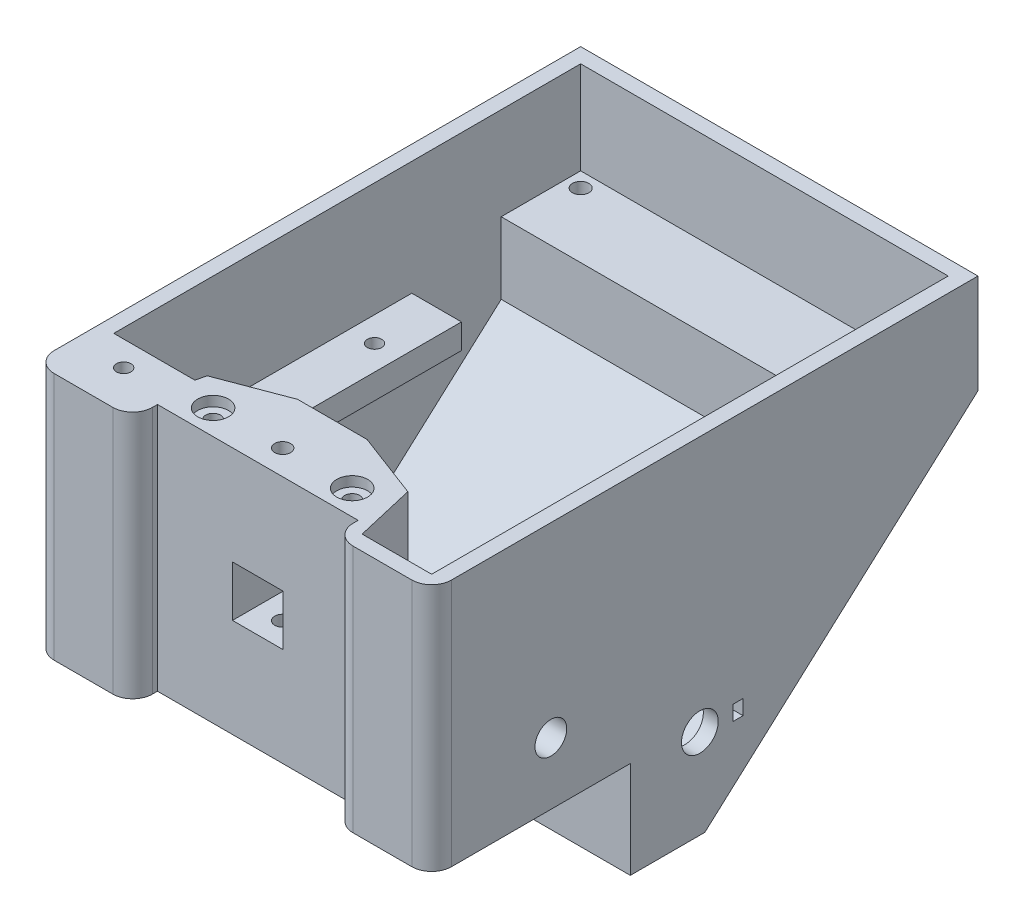
SolidWorks part; units mm, degrees
ref_plane "Спереди" through (0, 0, 0) normal (0, 0, 1) x (1, 0, 0)
ref_plane "Сверху" through (0, 0, 0) normal (0, 1, 0) x (1, 0, 0)
ref_plane "Справа" through (0, 0, 0) normal (1, 0, 0) x (0, 0, -1)
sketch "Sketch2" plane through (0, 0, 0) normal (1, 0, 0) x (0, 0, -1)
  line L0 (-27.3205, 20.9982) -> (-27.3205, -29.0018)
  line L1 (-27.3205, -29.0018) -> (12.6795, -29.0018)
  line L2 (12.6795, -29.0018) -> (12.6795, -48.5114)
  line L3 (12.6795, -48.5114) -> (27.6795, -48.5114)
  line L4 (82.6795, 20.9982) -> (82.6795, 0.9982)
  line L5 (82.6795, 20.9982) -> (-27.3205, 20.9982)
  line L6 (82.6795, 0.9982) -> (27.6795, -48.5114)
  dimension "D1" = 110
  dimension "D2" = 50
  dimension "D3" = 40
  dimension "D4" = 15
  dimension "D5" = 20
extrude "Boss-Extrude1" add sketch "Sketch2" along normal blind 80
shell "Shell1" thickness 3
sketch "Sketch3" plane through (0, 0, 24.3205) normal (0, 0, -1) x (-1, 0, 0)
  line L0 (-40, 20.9982) -> (-40, -26.0018) construction
  line L3 (-77, 20.9982) -> (-3, 20.9982) construction
  line L4 (-77, -26.0018) -> (-3, -26.0018) construction
  line L6 (-17, 20.9982) -> (-63, 20.9982)
  line L7 (-17, 20.9982) -> (-17, -26.0018)
  line L8 (-17, -26.0018) -> (-63, -26.0018)
  line L9 (-63, 20.9982) -> (-63, -26.0018)
  line L10 (-17, 20.9982) -> (-63, -26.0018) construction
  line L11 (-17, -26.0018) -> (-63, 20.9982) construction
  point P6 (-40, -2.5018)
  dimension "D1" = 46
extrude "Boss-Extrude2" add sketch "Sketch3" along normal blind 17
sketch "Sketch4" plane through (0, 0, 27.3205) normal (0, 0, 1) x (1, 0, 0)
  line L0 (0, 20.9982) -> (80, -29.0018) construction
  line L2 (45.1, -9.1018) -> (34.9, -9.1018)
  line L3 (45.1, -9.1018) -> (45.1, 1.0982)
  line L4 (45.1, 1.0982) -> (34.9, 1.0982)
  line L5 (34.9, -9.1018) -> (34.9, 1.0982)
  line L6 (45.1, -9.1018) -> (34.9, 1.0982) construction
  line L7 (45.1, 1.0982) -> (34.9, -9.1018) construction
  point P4 (40, -4.0018)
  dimension "D1" = 10.2
extrude "Cut-Extrude1" cut sketch "Sketch4" against normal up to surface (20 mm away) up to face at (40, -2.5018, 7.3205)
sketch "Sketch6" plane through (0, -29.0018, 0) normal (0, -1, 0) x (1, 0, 0)
  line L0 (40, 27.3205) -> (40, -12.6795) construction
  line L1 (47.5, -5.4795) -> (32.5, -5.4795)
  line L2 (47.5, -5.4795) -> (47.5, 7.3205)
  line L3 (47.5, 7.3205) -> (32.5, 7.3205)
  line L4 (32.5, -5.4795) -> (32.5, 7.3205)
  line L5 (47.5, -5.4795) -> (32.5, 7.3205) construction
  line L6 (47.5, 7.3205) -> (32.5, -5.4795) construction
  line L7 (80, -12.6795) -> (0, -12.6795) construction
  line L9 (80, 27.3205) -> (0, 27.3205) construction
  point P0 (40, 0.9205)
  dimension "D1" = 15
  dimension "D2" = 12.8
  dimension "D4" = 20
extrude "Cut-Extrude2" cut sketch "Sketch6" against normal up to surface (3 mm away) up to face at (40, -26.0018, 10.0705)
sketch "Sketch7" plane through (0, 0, 27.3205) normal (0, 0, 1) x (1, 0, 0)
  line L0 (40, 20.9982) -> (40, -29.0018) construction
  line L1 (80, 20.9982) -> (0, 20.9982) construction
  line L2 (80, -29.0018) -> (0, -29.0018) construction
  line L4 (60.2, -29.0018) -> (19.8, -29.0018)
  line L5 (60.2, -29.0018) -> (60.2, 20.9982)
  line L6 (60.2, 20.9982) -> (19.8, 20.9982)
  line L7 (19.8, -29.0018) -> (19.8, 20.9982)
  line L8 (60.2, -29.0018) -> (19.8, 20.9982) construction
  line L9 (60.2, 20.9982) -> (19.8, -29.0018) construction
  point P6 (40, -4.0018)
  dimension "D1" = 40.4
extrude "Cut-Extrude3" cut sketch "Sketch7" against normal blind 5
fillet "Fillet1" radius 4 4 edges at (19.8, -4.0018, 27.3205) (60.2, -4.0018, 27.3205) (80, -4.0018, 27.3205) (0, -4.0018, 27.3205)
sketch "Sketch12" plane through (0, 20.9982, 0) normal (0, 1, 0) x (1, 0, 0)
  line L0 (19.8, -22.3205) -> (19.8, -12.3205) construction
  line L1 (19.8, -12.3205) -> (60.2, -12.3205) construction
  line L2 (60.2, -12.3205) -> (60.2, -22.3205) construction
  line L3 (33, -7.3205) -> (19.8, -12.3205)
  line L4 (17, -7.3205) -> (63, -7.3205) construction
  line L5 (19.8, -12.3205) -> (17, -24.3205)
  line L6 (17, -24.3205) -> (17, -7.3205)
  line L7 (17, -7.3205) -> (33, -7.3205)
  line L8 (47, -7.3205) -> (63, -7.3205)
  line L9 (63, -7.3205) -> (63, -24.3205)
  line L10 (63, -24.3205) -> (60.2, -12.3205)
  line L11 (60.2, -12.3205) -> (47, -7.3205)
  dimension "D1" = 10
  dimension "D2" = 16
extrude "Cut-Extrude7" cut sketch "Sketch12" against normal up to surface (47 mm away) up to face at (40, -26.0018, 7.0205)
sketch "Sketch13" plane through (0, 20.9982, 0) normal (0, 1, 0) x (1, 0, 0)
  line L0 (19.8, -22.3205) -> (19.8, -12.3205) construction
  line L1 (19.8, -12.3205) -> (60.2, -12.3205) construction
  line L2 (60.2, -12.3205) -> (60.2, -22.3205) construction
  line L3 (60.2, -17.3205) -> (19.8, -17.3205) construction
  circle A0 centre (26, -17.3205) radius 1.5
  circle A1 centre (54, -17.3205) radius 1.5
  point P14 (40, -17.3205)
  dimension "D1" = 3
  dimension "D2" = 28
  dimension "D3" = 14
  dimension "D4" = 6.2
extrude "Cut-Extrude8" cut sketch "Sketch13" against normal blind 25
sketch "Sketch14" plane through (0, 20.9982, 0) normal (0, 1, 0) x (1, 0, 0)
  circle A0 centre (26, -17.3205) radius 3.1
  circle A1 centre (54, -17.3205) radius 3.1
  dimension "D1" = 6.2
extrude "Cut-Extrude9" cut sketch "Sketch14" against normal blind 2
sketch "Sketch17" plane through (77, 0, 0) normal (-1, 0, 0) x (0, 0, 1)
  line L0 (-45.6795, -2.0018) -> (-0.6795, -2.0018)
  line L1 (-0.6795, -2.0018) -> (-0.6795, -7.0018)
  line L2 (-0.6795, -7.0018) -> (-45.6795, -7.0018)
  line L3 (-45.6795, -7.0018) -> (-45.6795, -2.0018)
  line L4 (-79.6795, 20.9982) -> (24.3205, 20.9982) construction
  line L5 (-79.6795, 2.3342) -> (-79.6795, 20.9982) construction
  dimension "D1" = 45
  dimension "D2" = 5
  dimension "D3" = 23
  dimension "D4" = 34
extrude "Boss-Extrude5" add sketch "Sketch17" along normal up to surface (74 mm away) up to face at (3, -14.0994, -24.0865)
sketch "Sketch18" plane through (0, -2.0018, 0) normal (0, 1, 0) x (1, 0, 0)
  line L0 (40, 0.6795) -> (40, 45.6795) construction
  line L1 (3, 0.6795) -> (77, 0.6795) construction
  line L2 (3, 45.6795) -> (77, 45.6795) construction
  line L3 (77, 0.6795) -> (77, 45.6795) construction
  line L4 (13, 0.6795) -> (67, 0.6795)
  line L5 (13, 0.6795) -> (13, 45.6795)
  line L6 (13, 45.6795) -> (67, 45.6795)
  line L7 (67, 0.6795) -> (67, 45.6795)
  line L8 (13, 0.6795) -> (67, 45.6795) construction
  line L9 (13, 45.6795) -> (67, 0.6795) construction
  point P6 (40, 23.1795)
  dimension "D1" = 10
extrude "Cut-Extrude10" cut sketch "Sketch18" against normal up to next
sketch "Sketch19" plane through (0, -2.0018, 0) normal (0, 1, 0) x (1, 0, 0)
  line L0 (72, 45.6795) -> (72, 0.6795) construction
  line L1 (67, 45.6795) -> (77, 45.6795) construction
  line L2 (67, 0.6795) -> (77, 0.6795) construction
  line L3 (8, 45.6795) -> (8, 0.6795) construction
  line L4 (3, 45.6795) -> (13, 45.6795) construction
  line L5 (3, 0.6795) -> (13, 0.6795) construction
  circle A0 centre (72, 37.1795) radius 1.45
  circle A1 centre (72, 6.1795) radius 1.45
  circle A2 centre (8, 33.1795) radius 1.45
  circle A3 centre (8, 6.1795) radius 1.45
  point P20 (72, 23.1795)
  point P21 (8, 23.1795)
  dimension "D1" = 2.9
  dimension "D2" = 14
  dimension "D3" = 17
  dimension "D4" = 17
  dimension "D5" = 10
extrude "Cut-Extrude11" cut sketch "Sketch19" against normal up to next
sketch "Sketch21" plane through (0, -26.0018, 0) normal (0, 1, 0) x (1, 0, 0)
  line L0 (3, -24.3205) -> (3, -14.3205)
  line L1 (3, -24.3205) -> (3, 15.6795) construction
  line L2 (3, -14.3205) -> (19.3333, -14.3205)
  line L3 (19.8, -12.3205) -> (17, -24.3205) construction
  line L4 (19.3333, -14.3205) -> (17, -24.3205)
  line L6 (3, -24.3205) -> (17, -24.3205)
  dimension "D1" = 10
extrude "Boss-Extrude6" add sketch "Sketch21" along normal up to surface (47 mm away) up to face at (54, 20.9982, 20.4205)
sketch "Sketch22" plane through (0, 20.9982, 0) normal (0, 1, 0) x (1, 0, 0)
  line L0 (0, 82.6795) -> (0, -23.3205) construction
  line L1 (15.8, -27.3205) -> (4, -27.3205) construction
  circle A0 centre (10, -19.3205) radius 1.45
  dimension "D1" = 2.9
  dimension "D2" = 10
  dimension "D3" = 8
extrude "Cut-Extrude12" cut sketch "Sketch22" against normal through all
sketch "Sketch24" plane through (80, 0, 0) normal (1, 0, 0) x (0, 0, -1)
  line L0 (12.6795, -48.5114) -> (27.6795, -48.5114) construction
  line L1 (12.6795, -29.0018) -> (12.6795, -48.5114) construction
  line L2 (18.1795, -30.5114) -> (18.1795, -19.0114) construction
  line L3 (18.1795, -19.0114) -> (35.1795, -19.0114) construction
  line L4 (35.1795, -19.0114) -> (35.1795, -30.5114) construction
  line L5 (26.6795, -19.0114) -> (26.6795, -39.0114) construction
  line L6 (30.3795, -30.5114) -> (34.3795, -30.5114) construction
  line L8 (33.3795, -32.0114) -> (35.3795, -32.0114)
  line L9 (33.3795, -32.0114) -> (33.3795, -29.0114)
  line L10 (33.3795, -29.0114) -> (35.3795, -29.0114)
  line L11 (35.3795, -32.0114) -> (35.3795, -29.0114)
  line L12 (33.3795, -32.0114) -> (35.3795, -29.0114) construction
  line L13 (33.3795, -29.0114) -> (35.3795, -32.0114) construction
  circle A0 centre (26.6795, -30.5114) radius 3.7
  circle A1 centre (26.6795, -30.5114) radius 8.5 construction
  dimension "D1" = 7.4
  dimension "D2" = 17
  dimension "D3" = 18
  dimension "D4" = 14
  dimension "D5" = 20
  dimension "D6" = 4
  dimension "D7" = 2
  dimension "D8" = 3
extrude "Cut-Extrude13" cut sketch "Sketch24" against normal up to next
sketch "Sketch26" plane through (3, 0, 0) normal (1, 0, 0) x (0, 0, -1)
  line L0 (79.6795, 2.3342) -> (63.6795, 2.3342)
  line L1 (63.6795, 2.3342) -> (63.6795, -12.0686)
  line L2 (26.5281, -45.5114) -> (79.6795, 2.3342) construction
  line L3 (63.6795, -12.0686) -> (79.6795, 2.3342)
  dimension "D1" = 16
extrude "Boss-Extrude7" add sketch "Sketch26" along normal up to surface (74 mm away) up to face at (77, -30.5114, -34.3795)
sketch "Sketch27" plane through (0, 2.3342, 0) normal (0, 1, 0) x (1, 0, 0)
  line L0 (3, 76.6795) -> (77, 76.6795) construction
  line L1 (3, 79.6795) -> (3, 63.6795) construction
  line L2 (77, 79.6795) -> (77, 63.6795) construction
  line L3 (80, 82.6795) -> (0, 82.6795) construction
  circle A0 centre (6, 76.6795) radius 1.65
  circle A1 centre (74, 76.6795) radius 1.65
  point P10 (40, 76.6795)
  dimension "D1" = 3.3
  dimension "D2" = 68
  dimension "D3" = 34
  dimension "D4" = 6
extrude "Cut-Extrude14" cut sketch "Sketch27" against normal blind 10
sketch "Sketch28" plane through (0, 2.3342, 0) normal (0, 1, 0) x (1, 0, 0)
  line L1 (74, 79.9295) -> (71.1854, 78.3045)
  line L2 (71.1854, 78.3045) -> (71.1854, 75.0545)
  line L3 (71.1854, 75.0545) -> (74, 73.4295)
  line L4 (74, 73.4295) -> (76.8146, 75.0545)
  line L5 (76.8146, 75.0545) -> (76.8146, 78.3045)
  line L6 (76.8146, 78.3045) -> (74, 79.9295)
  line L7 (6, 73.4295) -> (8.8146, 75.0545)
  line L8 (8.8146, 75.0545) -> (8.8146, 78.3045)
  line L9 (8.8146, 78.3045) -> (6, 79.9295)
  line L10 (6, 79.9295) -> (3.1854, 78.3045)
  line L11 (3.1854, 78.3045) -> (3.1854, 75.0545)
  line L12 (3.1854, 75.0545) -> (6, 73.4295)
  circle A0 centre (74, 76.6795) radius 3.25 construction
  circle A1 centre (6, 76.6795) radius 3.25 construction
  dimension "D1" = 6.5
extrude "Cut-Extrude15" cut sketch "Sketch28" against normal blind 32 from offset 3 offset against normal yes
sketch "Sketch29" plane through (0, -29.0018, 0) normal (0, -1, 0) x (1, 0, 0)
  line L0 (0, 23.3205) -> (0, -12.6795) construction
  line L1 (7.1854, 17.6955) -> (10, 16.0705)
  line L2 (10, 16.0705) -> (12.8146, 17.6955)
  line L3 (12.8146, 17.6955) -> (12.8146, 20.9455)
  line L4 (12.8146, 20.9455) -> (10, 22.5705)
  line L5 (10, 22.5705) -> (7.1854, 20.9455)
  line L6 (7.1854, 20.9455) -> (7.1854, 17.6955)
  circle A0 centre (10, 19.3205) radius 3.25 construction
  dimension "D1" = 6.5
extrude "Cut-Extrude16" cut sketch "Sketch29" against normal blind 30
sketch "Sketch30" plane through (0, -26.0018, 0) normal (0, 1, 0) x (1, 0, 0)
  line L0 (77, -24.3205) -> (63, -24.3205)
  line L1 (63, -24.3205) -> (60.2, -12.3205)
  line L2 (63, -24.3205) -> (60.2, -12.3205) construction
  line L3 (60.2, -12.3205) -> (77, -12.3205)
  line L4 (77, -24.3205) -> (77, 15.6795) construction
  line L5 (77, -12.3205) -> (77, -24.3205)
  dimension "D1" = 12
extrude "Boss-Extrude8" add sketch "Sketch30" along normal blind 20
sketch "Sketch31" plane through (0, -6.0018, 0) normal (0, 1, 0) x (1, 0, 0)
  line L0 (76, -27.3205) -> (64.2, -27.3205) construction
  line L1 (80, -23.3205) -> (80, 12.6795) construction
  circle A0 centre (72, -21.3205) radius 1.5
  dimension "D3" = 3
  dimension "D1" = 6
  dimension "D2" = 8
extrude "Cut-Extrude17" cut sketch "Sketch31" against normal through all
sketch "Sketch32" plane through (0, -29.0018, 0) normal (0, -1, 0) x (1, 0, 0)
  line L1 (72, 24.5705) -> (69.1854, 22.9455)
  line L2 (69.1854, 22.9455) -> (69.1854, 19.6955)
  line L3 (69.1854, 19.6955) -> (72, 18.0705)
  line L4 (72, 18.0705) -> (74.8146, 19.6955)
  line L5 (74.8146, 19.6955) -> (74.8146, 22.9455)
  line L6 (74.8146, 22.9455) -> (72, 24.5705)
  circle A0 centre (72, 21.3205) radius 3.25 construction
  dimension "D1" = 6.5
extrude "Cut-Extrude18" cut sketch "Sketch32" against normal blind 15
sketch "Sketch33" plane through (0, -2.0018, 0) normal (0, 1, 0) x (1, 0, 0)
  line L0 (67, 40.6795) -> (77, 40.6795)
  line L1 (67, 0.6795) -> (67, 45.6795) construction
  line L2 (77, 0.6795) -> (77, 45.6795) construction
  line L3 (77, 40.6795) -> (77, 45.6795)
  line L4 (77, 45.6795) -> (67, 45.6795)
  line L5 (67, 45.6795) -> (67, 40.6795)
  dimension "D1" = 5
extrude "Cut-Extrude19" cut sketch "Sketch33" against normal up to next
sketch "Sketch34" plane through (0, 20.9982, 0) normal (0, 1, 0) x (1, 0, 0)
  line L0 (54, -17.3205) -> (26, -17.3205) construction
  circle A0 centre (40, -17.3205) radius 1.6
  dimension "D1" = 3.2
extrude "Cut-Extrude20" cut sketch "Sketch34" against normal through all
sketch "Sketch36" plane through (0, -29.0018, 0) normal (0, -1, 0) x (1, 0, 0)
  line L1 (38.375, 20.1351) -> (36.75, 17.3205)
  line L2 (36.75, 17.3205) -> (38.375, 14.5059)
  line L3 (38.375, 14.5059) -> (41.625, 14.5059)
  line L4 (41.625, 14.5059) -> (43.25, 17.3205)
  line L5 (43.25, 17.3205) -> (41.625, 20.1351)
  line L6 (41.625, 20.1351) -> (38.375, 20.1351)
  circle A0 centre (40, 17.3205) radius 3.25 construction
  dimension "D1" = 6.5
extrude "Cut-Extrude22" cut sketch "Sketch36" against normal blind 14
sketch "Sketch37" plane through (80, 0, 0) normal (1, 0, 0) x (0, 0, -1)
  line L0 (-23.3205, -16.5114) -> (63.2281, -16.5114) construction
  line L1 (-23.3205, 20.9982) -> (-23.3205, -29.0018) construction
  line L2 (27.6795, -48.5114) -> (82.6795, 0.9982) construction
  line L3 (30.3795, -30.5114) -> (22.9795, -30.5114) construction
  circle A0 centre (-3.3205, -16.5114) radius 3.2
  circle A1 centre (26.6795, -30.5114) radius 3.7 construction
  point P14 (26.6795, -30.5114)
  dimension "D1" = 6.4
  dimension "D2" = 14
  dimension "D3" = 20
extrude "Cut-Extrude23" cut sketch "Sketch37" against normal up to next
sketch "Sketch38" plane through (77, 0, 0) normal (-1, 0, 0) x (0, 0, 1)
  line L0 (12.3205, -26.0018) -> (-15.6795, -26.0018) construction
  line L1 (8.3205, -7.021) -> (-1.6795, -7.021)
  line L2 (8.3205, -7.021) -> (8.3205, -26.0018)
  line L3 (8.3205, -26.0018) -> (-1.6795, -26.0018)
  line L4 (-1.6795, -7.021) -> (-1.6795, -26.0018)
  line L5 (8.3205, -7.021) -> (-1.6795, -26.0018) construction
  line L6 (8.3205, -26.0018) -> (-1.6795, -7.021) construction
  circle A0 centre (3.3205, -16.5114) radius 3.2
  point P0 (3.3205, -16.5114)
  dimension "D1" = 10
extrude "Boss-Extrude9" add sketch "Sketch38" along normal blind 3
sketch "Sketch40" plane through (3, 0, 0) normal (1, 0, 0) x (0, 0, -1)
  line L0 (18.1795, -30.5114) -> (18.1795, -19.0114) construction
  line L1 (18.1795, -19.0114) -> (35.1795, -19.0114) construction
  line L2 (35.1795, -19.0114) -> (35.1795, -30.5114) construction
  line L3 (26.6795, -19.0114) -> (26.6795, -39.0114) construction
  line L4 (30.3795, -30.5114) -> (34.3795, -30.5114) construction
  line L5 (33.3795, -32.0114) -> (35.3795, -32.0114) construction
  line L6 (33.3795, -32.0114) -> (33.3795, -29.0114) construction
  line L7 (33.3795, -29.0114) -> (35.3795, -29.0114) construction
  line L8 (35.3795, -32.0114) -> (35.3795, -29.0114) construction
  line L9 (33.3795, -32.0114) -> (35.3795, -29.0114) construction
  line L10 (33.3795, -29.0114) -> (35.3795, -32.0114) construction
  line L13 (22.9795, -30.5114) -> (18.9795, -30.5114) construction
  line L14 (12.6795, -29.0018) -> (12.6795, -48.5114) construction
  line L15 (17.9795, -29.0114) -> (19.9795, -29.0114)
  line L16 (17.9795, -29.0114) -> (17.9795, -32.0114)
  line L17 (17.9795, -32.0114) -> (19.9795, -32.0114)
  line L18 (19.9795, -29.0114) -> (19.9795, -32.0114)
  line L19 (17.9795, -29.0114) -> (19.9795, -32.0114) construction
  line L20 (17.9795, -32.0114) -> (19.9795, -29.0114) construction
  line L21 (12.6795, -48.5114) -> (27.6795, -48.5114) construction
  circle A0 centre (26.6795, -30.5114) radius 3.7
  circle A1 centre (26.6795, -30.5114) radius 8.5 construction
  dimension "D4" = 17
  dimension "D5" = 17
  dimension "D11" = 7.4
  dimension "D1" = 3
  dimension "D2" = 2
  dimension "D3" = 4
  dimension "D6" = 2
  dimension "D7" = 3
  dimension "D8" = 4
  dimension "D9" = 14
  dimension "D10" = 18
extrude "Cut-Extrude24" cut sketch "Sketch40" against normal up to next
